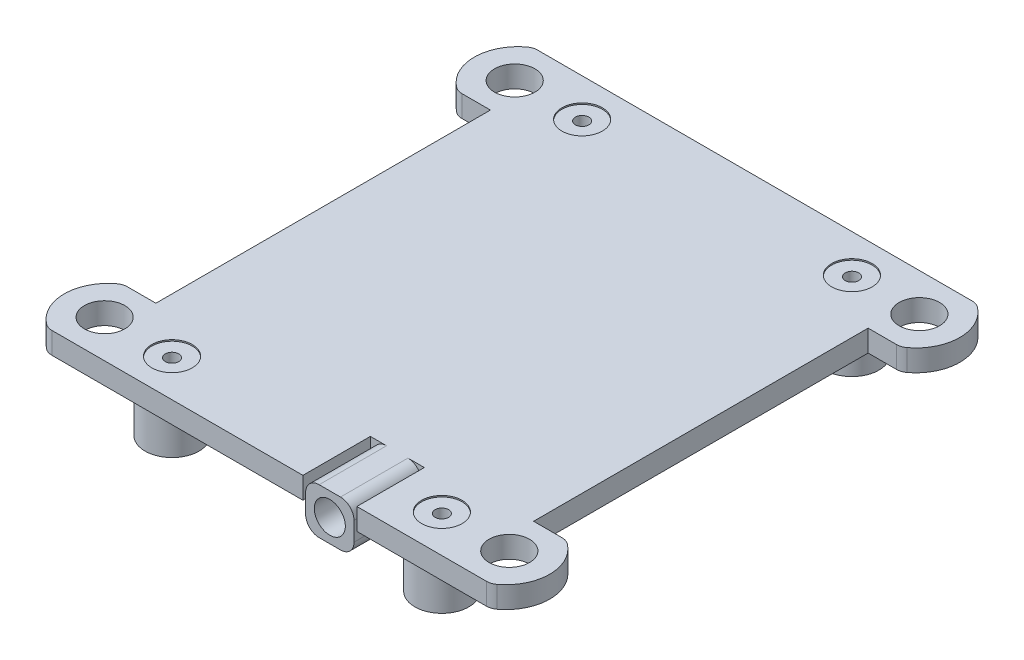
SolidWorks part; units mm, degrees
ref_plane "Front Plane" through (0, 0, 0) normal (0, 0, 1) x (1, 0, 0)
ref_plane "Top Plane" through (0, 0, 0) normal (0, 1, 0) x (1, 0, 0)
ref_plane "Right Plane" through (0, 0, 0) normal (1, 0, 0) x (0, 0, -1)
sketch "Sketch1" plane through (0, 0, 0) normal (0, 1, 0) x (1, 0, 0)
  line L0 (0, 0) -> (0, 18) construction
  line L1 (14, -18) -> (-14, -18)
  line L2 (14, -18) -> (14, 18)
  line L3 (14, 18) -> (-14, 18)
  line L4 (-14, -18) -> (-14, 18)
  line L5 (14, -18) -> (-14, 18) construction
  line L6 (14, 18) -> (-14, -18) construction
  line L7 (0, 0) -> (14, 0) construction
  line L8 (-14, 18) -> (-16.1, 18)
  line L9 (-15, 15.2) -> (15, 15.2) construction
  line L10 (-14, 12.4) -> (-16.1, 12.4)
  line L11 (14, 18) -> (16.1, 18)
  line L12 (14, 12.4) -> (16.1, 12.4)
  line L13 (-15, -15.2) -> (15, -15.2) construction
  line L14 (-14, -18) -> (-16.1, -18)
  line L15 (14, -18) -> (16.1, -18)
  line L16 (-14, -12.4) -> (-16.1, -12.4)
  line L17 (14, -12.4) -> (16.1, -12.4)
  circle A0 centre (-15, 15.2) radius 1.5
  circle A1 centre (15, 15.2) radius 1.5
  circle A2 centre (15, -15.2) radius 1.5
  circle A3 centre (-15, -15.2) radius 1.5
  arc A4 (-16.7, 17.8) -> (-16.7, 12.6) centre (-14.75, 15.2) ccw
  arc A5 (16.7, 17.8) -> (16.7, 12.6) centre (14.75, 15.2) cw
  arc A8 (-16.7, -17.8) -> (-16.7, -12.6) centre (-14.75, -15.2) cw
  arc A9 (16.7, -17.8) -> (16.7, -12.6) centre (14.75, -15.2) ccw
  arc A10 (16.1, -18) -> (16.7, -17.8) centre (16.1, -17) ccw
  arc A11 (16.7, -12.6) -> (16.1, -12.4) centre (16.1, -13.4) ccw
  arc A12 (-16.1, -18) -> (-16.7, -17.8) centre (-16.1, -17) cw
  arc A13 (-16.7, -12.6) -> (-16.1, -12.4) centre (-16.1, -13.4) cw
  arc A14 (16.7, 12.6) -> (16.1, 12.4) centre (16.1, 13.4) cw
  arc A15 (16.7, 17.8) -> (16.1, 18) centre (16.1, 17) ccw
  arc A16 (-16.1, 12.4) -> (-16.7, 12.6) centre (-16.1, 13.4) cw
  arc A17 (-16.1, 18) -> (-16.7, 17.8) centre (-16.1, 17) ccw
  circle A18 centre (-10, 15.2) radius 0.5
  circle A19 centre (10, 15.2) radius 0.5
  circle A20 centre (10, -15.2) radius 0.5
  circle A21 centre (-10, -15.2) radius 0.5
  point P0 (0, 0)
  point P22 (16.4, -18)
  point P38 (16.4, -12.4)
  point P41 (-16.4, -18)
  point P44 (-16.4, -12.4)
  point P47 (16.4, 12.4)
  point P50 (16.4, 18)
  point P53 (-16.4, 12.4)
  point P56 (-16.4, 18)
  dimension "D3" = 3
  dimension "D6" = 6.5
  dimension "D8" = 1
  dimension "D9" = 1
  dimension "D1" = 36
  dimension "D2" = 28
  dimension "D4" = 30.4
  dimension "D5" = 30
  dimension "D7" = 29.5
  dimension "D10" = 20
extrude "Boss-Extrude1" add sketch "Sketch1" against normal blind 1.6 contours L4 A3 L1 L2 A2 A1 L3 A0 A19 A18 A20 A21 | A13 A8 A12 L14 L4 A3 L16 | L8 A17 A4 A16 L10 L4 A0 | A5 A15 L11 L2 A1 L12 A14 | A9 A11 L17 L2 A2 L15 A10
sketch "Sketch2" plane through (0, -1.6, 0) normal (0, -1, 0) x (1, 0, 0)
  line L0 (0, 0) -> (0, 18) construction
  line L1 (16.1, 18) -> (-16.1, 18) construction
  line L2 (0, 0) -> (14, 0) construction
  line L3 (14, 12.4) -> (14, -12.4) construction
  circle A0 centre (-10, 15.2) radius 2
  circle A1 centre (10, 15.2) radius 2
  circle A2 centre (10, -15.2) radius 2
  circle A3 centre (-10, -15.2) radius 2
  circle A4 centre (10, -15.2) radius 0.5 construction
  circle A5 centre (-10, -15.2) radius 0.5 construction
  circle A6 centre (10, 15.2) radius 0.5 construction
  circle A7 centre (-10, 15.2) radius 0.5 construction
  circle A8 centre (10, -15.2) radius 0.5
  circle A9 centre (-10, -15.2) radius 0.5
  circle A10 centre (10, 15.2) radius 0.5
  circle A11 centre (-10, 15.2) radius 0.5
  dimension "D1" = 4
extrude "Boss-Extrude2" add sketch "Sketch2" along normal blind 3.5
sketch "Sketch3" plane through (0, 0, 0) normal (0, 1, 0) x (1, 0, 0)
  line L0 (0, 0) -> (14, 0) construction
  line L1 (0, 15.2) -> (0, 0) construction
  line L2 (14, -12.4) -> (14, 12.4) construction
  circle A0 centre (-10, 15.2) radius 1.5
  circle A1 centre (10, 15.2) radius 1.5
  circle A2 centre (10, -15.2) radius 1.5
  circle A3 centre (-10, -15.2) radius 1.5
  circle A4 centre (10, -15.2) radius 0.5 construction
  circle A5 centre (-10, -15.2) radius 0.5 construction
  circle A6 centre (10, 15.2) radius 0.5 construction
  circle A7 centre (-10, 15.2) radius 0.5 construction
  circle A8 centre (10, -15.2) radius 0.5
  circle A9 centre (-10, -15.2) radius 0.5
  circle A10 centre (10, 15.2) radius 0.5
  circle A11 centre (-10, 15.2) radius 0.5
  dimension "D1" = 3
extrude "Cut-Extrude1" cut sketch "Sketch3" against normal blind 0.1
sketch "Sketch4" plane through (0, -1.6, 0) normal (0, -1, 0) x (1, 0, 0)
  line L0 (-14, 12.4) -> (-14, -12.4) construction
  line L1 (-14, 8) -> (-11.1851, 8)
  line L2 (-14, 8) -> (-14, 3)
  line L3 (-14, 3) -> (-11.1851, 3)
  line L4 (-11.1851, 8) -> (-11.1851, 3)
  line L5 (16.1, 18) -> (-16.1, 18) construction
  dimension "D1" = 10
  dimension "D2" = 5
extrude "Boss-Extrude3" add sketch "Sketch4" along normal blind 1.5
sketch "Sketch5" plane through (-14, 0, 0) normal (-1, 0, 0) x (0, 0, 1)
  line L0 (3, -1.6) -> (8, -3.1) construction
  line L1 (3, -3.1) -> (8, -1.6) construction
  line L3 (6.3, -2.75) -> (4.7, -2.75)
  line L4 (6.3, -2.75) -> (6.3, -1.95)
  line L5 (6.3, -1.95) -> (4.7, -1.95)
  line L6 (4.7, -2.75) -> (4.7, -1.95)
  line L7 (6.3, -2.75) -> (4.7, -1.95) construction
  line L8 (6.3, -1.95) -> (4.7, -2.75) construction
  point P8 (5.5, -2.35)
  dimension "D1" = 0.8
  dimension "D2" = 1.6
extrude "Boss-Extrude4" add sketch "Sketch5" along normal blind 0.5
sketch "Sketch6" plane through (0, -1.6, 0) normal (0, -1, 0) x (1, 0, 0)
  line L1 (-9.1804, 1.5572) -> (-4.6804, 1.5572)
  line L2 (-10.1804, 0.5572) -> (-10.1804, -3.9428)
  line L3 (-9.1804, -4.9428) -> (-4.6804, -4.9428)
  line L4 (-3.6804, 0.5572) -> (-3.6804, -3.9428)
  line L5 (-10.1804, 1.5572) -> (-3.6804, -4.9428) construction
  line L6 (-10.1804, -4.9428) -> (-3.6804, 1.5572) construction
  arc A0 (-4.6804, -4.9428) -> (-3.6804, -3.9428) centre (-4.6804, -3.9428) ccw
  arc A1 (-9.1804, -4.9428) -> (-10.1804, -3.9428) centre (-9.1804, -3.9428) cw
  arc A2 (-3.6804, 0.5572) -> (-4.6804, 1.5572) centre (-4.6804, 0.5572) ccw
  arc A3 (-9.1804, 1.5572) -> (-10.1804, 0.5572) centre (-9.1804, 0.5572) ccw
  point P0 (-6.9304, -1.6928)
  dimension "D3" = 1
  dimension "D1" = 6.5
  dimension "D2" = 6.5
extrude "Boss-Extrude5" add sketch "Sketch6" along normal blind 2.5
sketch "Sketch7" plane through (0, -1.6, 0) normal (0, -1, 0) x (1, 0, 0)
  line L1 (-1.5135, 5.08) -> (11.4865, 5.08)
  line L2 (-1.5135, 5.08) -> (-1.5135, -7.92)
  line L3 (-1.5135, -7.92) -> (11.4865, -7.92)
  line L4 (11.4865, 5.08) -> (11.4865, -7.92)
  line L5 (-1.5135, 5.08) -> (11.4865, -7.92) construction
  line L6 (-1.5135, -7.92) -> (11.4865, 5.08) construction
  point P0 (4.9865, -1.42)
  dimension "D1" = 13
  dimension "D2" = 13
extrude "Boss-Extrude6" add sketch "Sketch7" along normal blind 1
sketch "Sketch8" plane through (0, 0, 18) normal (0, 0, 1) x (1, 0, 0)
  line L0 (16.1, -1.6) -> (-16.1, -1.6) construction
  line L1 (6.5, -1.6) -> (2.5, -1.6)
  line L2 (6.5, -1.6) -> (6.5, 0)
  line L3 (6.5, 0) -> (2.5, 0)
  line L4 (2.5, -1.6) -> (2.5, 0)
  line L5 (16.1, 0) -> (-16.1, 0) construction
  line L6 (18, -1.6) -> (18, 0) construction
  dimension "D1" = 15.5
  dimension "D2" = 4
extrude "Cut-Extrude2" cut sketch "Sketch8" against normal blind 5
sketch "Sketch9" plane through (0, 0, 13) normal (0, 0, 1) x (1, 0, 0)
  line L0 (6.5, 0) -> (2.5, 0) construction
  line L5 (3.7021, 0) -> (5.2871, 0)
  line L6 (2.7021, -1) -> (2.7021, -2.4)
  line L7 (3.7021, -3.4) -> (5.2871, -3.4)
  line L8 (6.2871, -1) -> (6.2871, -2.4)
  arc A0 (3.7021, 0) -> (2.7021, -1) centre (3.7021, -1) ccw
  arc A1 (5.2871, 0) -> (6.2871, -1) centre (5.2871, -1) cw
  arc A2 (2.7021, -2.4) -> (3.7021, -3.4) centre (3.7021, -2.4) ccw
  arc A3 (5.2871, -3.4) -> (6.2871, -2.4) centre (5.2871, -2.4) ccw
  point P9 (2.7021, 0)
  dimension "D2" = 1
  dimension "D1" = 3.4
extrude "Boss-Extrude8" add sketch "Sketch9" along normal blind 5
sketch "Sketch10" plane through (0, 0, 18) normal (0, 0, 1) x (1, 0, 0)
  line L0 (4.4946, 0) -> (4.4946, -3.4) construction
  line L1 (5.2871, 0) -> (3.7021, 0) construction
  line L2 (3.7021, -3.4) -> (5.2871, -3.4) construction
  circle A0 centre (4.4946, -1.7) radius 1.15
  dimension "D1" = 2.3
extrude "Cut-Extrude3" cut sketch "Sketch10" against normal blind 4
sketch "Sketch11" plane through (0, 0, -18) normal (0, 0, -1) x (-1, 0, 0)
  line L0 (0, 0) -> (0, -1.6) construction
  line L1 (-16.1, 0) -> (16.1, 0) construction
  line L2 (-16.1, -1.6) -> (16.1, -1.6) construction
  line L4 (6.3, -4.9) -> (-6.3, -4.9)
  line L5 (6.3, -4.9) -> (6.3, -1.6)
  line L6 (6.3, -1.6) -> (-6.3, -1.6)
  line L7 (-6.3, -4.9) -> (-6.3, -1.6)
  line L8 (6.3, -4.9) -> (-6.3, -1.6) construction
  line L9 (6.3, -1.6) -> (-6.3, -4.9) construction
  point P6 (0, -3.25)
  dimension "D1" = 12.6
  dimension "D2" = 3.3
extrude "Boss-Extrude9" add sketch "Sketch11" against normal blind 5
sketch "Sketch12" plane through (0, 0, -18) normal (0, 0, -1) x (-1, 0, 0)
  line L0 (6.3, -1.6) -> (-6.3, -1.6) construction
  line L1 (-6.3, -1.6) -> (6.3, -4.9) construction
  line L2 (-6.3, -4.9) -> (6.3, -4.9) construction
  line L3 (-5.8, -2.1) -> (5.8, -2.1)
  line L4 (-5.8, -2.1) -> (-5.8, -4.4)
  line L5 (-5.8, -4.4) -> (5.8, -4.4)
  line L6 (5.8, -2.1) -> (5.8, -4.4)
  line L7 (-5.8, -2.1) -> (5.8, -4.4) construction
  line L8 (-5.8, -4.4) -> (5.8, -2.1) construction
  line L9 (6.3, -4.9) -> (6.3, -1.6) construction
  point P4 (0, -3.25)
  dimension "D1" = 0.5
  dimension "D2" = 0.5
extrude "Cut-Extrude4" cut sketch "Sketch12" against normal blind 4
sketch "Sketch13" plane through (0, 0, -14) normal (0, 0, -1) x (-1, 0, 0)
  line L0 (-3.3492, -3.0069) -> (-3.5304, -2.2115) construction
  line L1 (-5.0492, -3.0069) -> (-5.2304, -3.0069)
  line L2 (-5.0492, -3.0069) -> (-5.0492, -2.2115)
  line L3 (-5.0492, -2.2115) -> (-5.2304, -2.2115)
  line L4 (-5.2304, -3.0069) -> (-5.2304, -2.2115)
  line L5 (-5.0492, -3.0069) -> (-5.2304, -2.2115) construction
  line L6 (-5.0492, -2.2115) -> (-5.2304, -3.0069) construction
  line L7 (-3.3492, -2.2115) -> (-3.5304, -3.0069) construction
  line L8 (-3.3492, -3.0069) -> (-3.3492, -2.2115)
  line L9 (-3.3492, -3.0069) -> (-3.5304, -3.0069)
  line L10 (-3.5304, -3.0069) -> (-3.5304, -2.2115)
  line L11 (-3.3492, -2.2115) -> (-3.5304, -2.2115)
  line L12 (-1.6492, -3.0069) -> (-1.8304, -2.2115) construction
  line L13 (-1.6492, -2.2115) -> (-1.8304, -3.0069) construction
  line L14 (-1.6492, -3.0069) -> (-1.6492, -2.2115)
  line L15 (-1.6492, -3.0069) -> (-1.8304, -3.0069)
  line L16 (-1.8304, -3.0069) -> (-1.8304, -2.2115)
  line L17 (-1.6492, -2.2115) -> (-1.8304, -2.2115)
  line L18 (0.0508, -3.0069) -> (-0.1304, -2.2115) construction
  line L19 (0.0508, -2.2115) -> (-0.1304, -3.0069) construction
  line L20 (0.0508, -3.0069) -> (0.0508, -2.2115)
  line L21 (0.0508, -3.0069) -> (-0.1304, -3.0069)
  line L22 (-0.1304, -3.0069) -> (-0.1304, -2.2115)
  line L23 (0.0508, -2.2115) -> (-0.1304, -2.2115)
  line L24 (1.7508, -3.0069) -> (1.5696, -2.2115) construction
  line L25 (1.7508, -2.2115) -> (1.5696, -3.0069) construction
  line L26 (1.7508, -3.0069) -> (1.7508, -2.2115)
  line L27 (1.7508, -3.0069) -> (1.5696, -3.0069)
  line L28 (1.5696, -3.0069) -> (1.5696, -2.2115)
  line L29 (1.7508, -2.2115) -> (1.5696, -2.2115)
  line L30 (3.4508, -3.0069) -> (3.2696, -2.2115) construction
  line L31 (3.4508, -2.2115) -> (3.2696, -3.0069) construction
  line L32 (3.4508, -3.0069) -> (3.4508, -2.2115)
  line L33 (3.4508, -3.0069) -> (3.2696, -3.0069)
  line L34 (3.2696, -3.0069) -> (3.2696, -2.2115)
  line L35 (3.4508, -2.2115) -> (3.2696, -2.2115)
  line L36 (5.1508, -3.0069) -> (4.9696, -2.2115) construction
  line L37 (5.1508, -2.2115) -> (4.9696, -3.0069) construction
  line L38 (5.1508, -3.0069) -> (5.1508, -2.2115)
  line L39 (5.1508, -3.0069) -> (4.9696, -3.0069)
  line L40 (4.9696, -3.0069) -> (4.9696, -2.2115)
  line L41 (5.1508, -2.2115) -> (4.9696, -2.2115)
  point P0 (-5.1398, -2.6092)
  point P6 (-3.4398, -2.6092)
  point P11 (-1.7398, -2.6092)
  point P16 (-0.0398, -2.6092)
  point P21 (1.6602, -2.6092)
  point P26 (3.3602, -2.6092)
  point P31 (5.0602, -2.6092)
  dimension "D1" = 7
extrude "Boss-Extrude10" add sketch "Sketch13" along normal blind 3.5
